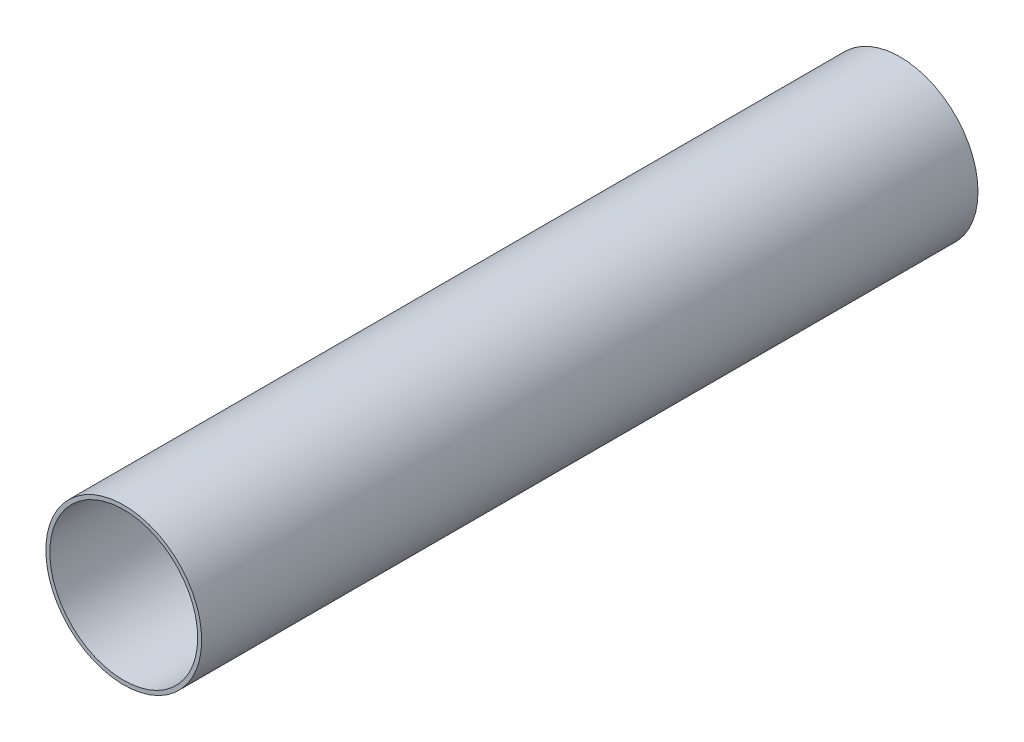
SolidWorks part; units mm, degrees
material "PVC Rigid"
ref_plane "Front Plane" through (0, 0, 0) normal (0, 0, 1) x (1, 0, 0)
ref_plane "Top Plane" through (0, 0, 0) normal (0, 1, 0) x (1, 0, 0)
ref_plane "Right Plane" through (0, 0, 0) normal (1, 0, 0) x (0, 0, -1)
sketch "Sketch1" plane through (0, 0, 0) normal (0, 0, 1) x (1, 0, 0)
  circle A0 centre (0, 0) radius 53.5305
  circle A2 centre (0, 0) radius 50.8
  dimension "D1" = 107.061
  dimension "D2" = 101.6
extrude "Boss-Extrude1" add sketch "Sketch1" along normal blind 533.4
